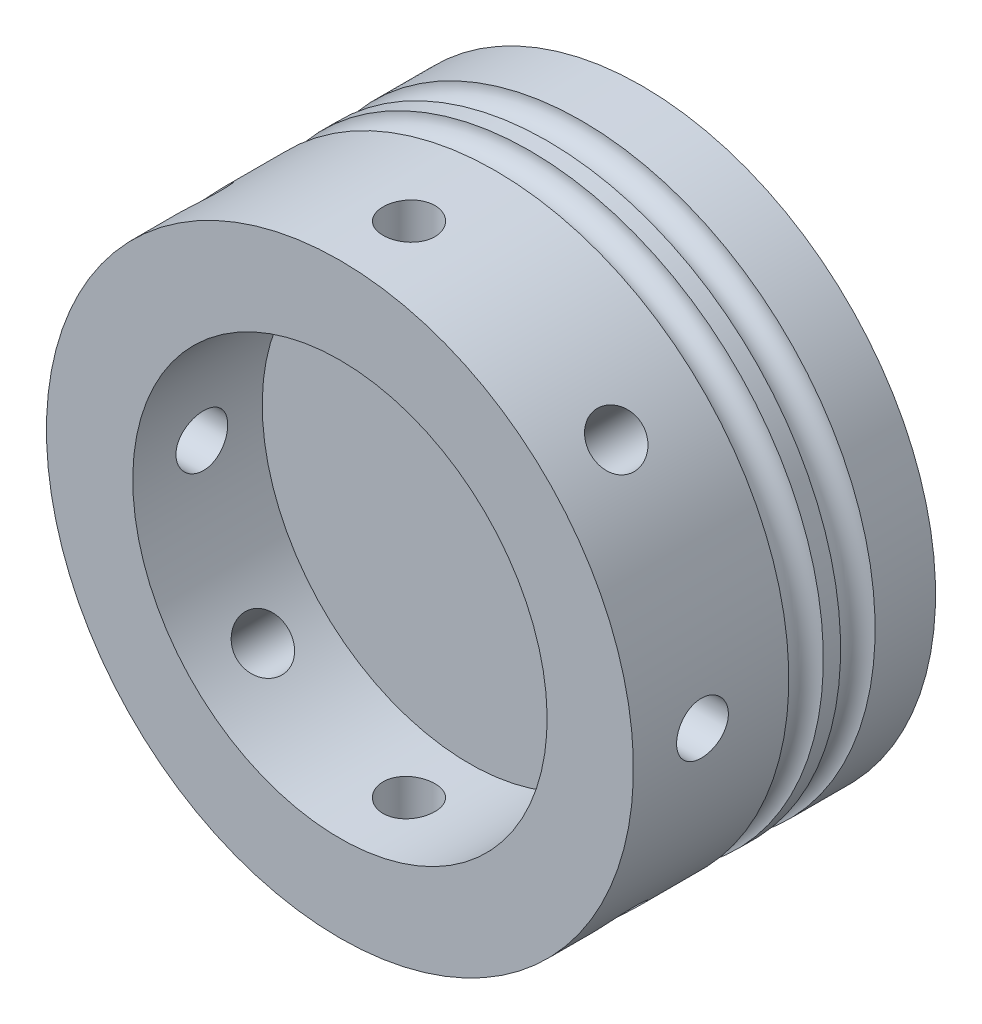
SolidWorks part; units mm, degrees
ref_plane "Front Plane" through (0, 0, 0) normal (0, 0, 1) x (1, 0, 0)
ref_plane "Top Plane" through (0, 0, 0) normal (0, 1, 0) x (1, 0, 0)
ref_plane "Right Plane" through (0, 0, 0) normal (1, 0, 0) x (0, 0, -1)
sketch "Sketch1" plane through (0, 0, 0) normal (1, 0, 0) x (0, 0, -1)
  line L0 (0, 0) -> (0, -10)
  line L1 (0, -10) -> (18, -10)
  line L2 (22, -10) -> (24, -10)
  line L3 (28, -10) -> (35, -10)
  line L4 (35, -10) -> (35, 24)
  line L7 (35, 24) -> (15, 24)
  line L8 (15, 24) -> (15, 0)
  line L9 (15, 0) -> (0, 0)
  arc A0 (18, -10) -> (22, -10) centre (20, -10) cw
  arc A1 (24, -10) -> (28, -10) centre (26, -10) cw
  dimension "D6" = 2
  dimension "D7" = 2
  dimension "D1" = 34
  dimension "D2" = 10
  dimension "D3" = 2
  dimension "D4" = 7
  dimension "D5" = 15
  dimension "D8" = 20
revolve "Revolve1" add sketch "Sketch1" angle 360 about L7
sketch "Sketch2" plane through (0, 0, 0) normal (0, 1, 0) x (1, 0, 0)
  circle A0 centre (0, 8) radius 3
  dimension "D1" = 6
  dimension "D2" = 8
  dimension "D3" = 0
extrude "Cut-Extrude3" cut sketch "Sketch2" against normal mid plane 25
pattern_circular "CirPattern1" count 8 over 360 about axis through (0, 24, -35) along (0, 0, -1) of "Cut-Extrude3"
